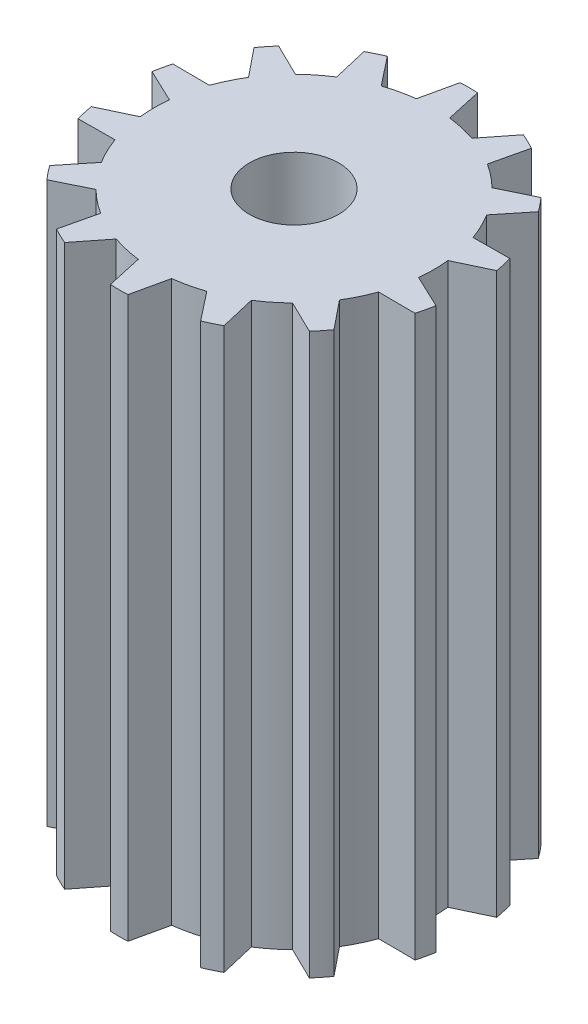
SolidWorks part; units mm, degrees
ref_plane "Front Plane" through (0, 0, 0) normal (0, 0, 1) x (1, 0, 0)
ref_plane "Top Plane" through (0, 0, 0) normal (0, 1, 0) x (1, 0, 0)
ref_plane "Right Plane" through (0, 0, 0) normal (1, 0, 0) x (0, 0, -1)
sketch "Sketch1" plane through (0, 0, 0) normal (0, 1, 0) x (1, 0, 0)
  line L0 (0, 0.0394) -> (0, 50000.0394) construction
  line L1 (0.0484, 0) -> (50000.0484, 0) construction
  line L30 (-0.25, 4.9937) -> (-0.4766, 3.9715)
  line L31 (0.25, 4.9937) -> (0.4766, 3.9715)
  line L32 (2.3919, 4.3907) -> (2.1526, 3.3714)
  line L33 (1.9415, 4.6077) -> (1.2937, 3.785)
  line L34 (4.0601, 2.9181) -> (3.4022, 2.1035)
  line L35 (3.7484, 3.309) -> (2.8079, 2.8488)
  line L36 (4.9242, 0.8675) -> (3.978, 0.4191)
  line L37 (4.8129, 1.3549) -> (3.7659, 1.3484)
  line L38 (4.8129, -1.3549) -> (3.7659, -1.3484)
  line L39 (4.9242, -0.8675) -> (3.978, -0.4191)
  line L40 (3.7484, -3.309) -> (2.8079, -2.8488)
  line L41 (4.0601, -2.9181) -> (3.4022, -2.1035)
  line L42 (1.9415, -4.6077) -> (1.2937, -3.785)
  line L43 (2.3919, -4.3907) -> (2.1526, -3.3714)
  line L44 (-0.25, -4.9937) -> (-0.4766, -3.9715)
  line L45 (0.25, -4.9937) -> (0.4766, -3.9715)
  line L46 (-2.3919, -4.3907) -> (-2.1526, -3.3714)
  line L47 (-1.9415, -4.6077) -> (-1.2937, -3.785)
  line L48 (-4.0601, -2.9181) -> (-3.4022, -2.1035)
  line L49 (-3.7484, -3.309) -> (-2.8079, -2.8488)
  line L50 (-4.9242, -0.8675) -> (-3.978, -0.4191)
  line L51 (-4.8129, -1.3549) -> (-3.7659, -1.3484)
  line L52 (-4.8129, 1.3549) -> (-3.7659, 1.3484)
  line L53 (-4.9242, 0.8675) -> (-3.978, 0.4191)
  line L54 (-3.7484, 3.309) -> (-2.8079, 2.8488)
  line L55 (-4.0601, 2.9181) -> (-3.4022, 2.1035)
  line L56 (-1.9415, 4.6077) -> (-1.2937, 3.785)
  line L57 (-2.3919, 4.3907) -> (-2.1526, 3.3714)
  circle A29 centre (0, 0) radius 4.5 construction
  arc A30 (-0.4766, 3.9715) -> (-1.2937, 3.785) centre (0, 0) ccw
  arc A31 (0.25, 4.9937) -> (-0.25, 4.9937) centre (0, 0) ccw
  arc A32 (2.3919, 4.3907) -> (1.9415, 4.6077) centre (0, 0) ccw
  arc A33 (4.0601, 2.9181) -> (3.7484, 3.309) centre (0, 0) ccw
  arc A34 (4.9242, 0.8675) -> (4.8129, 1.3549) centre (0, 0) ccw
  arc A35 (4.8129, -1.3549) -> (4.9242, -0.8675) centre (0, 0) ccw
  arc A36 (3.7484, -3.309) -> (4.0601, -2.9181) centre (0, 0) ccw
  arc A37 (1.9415, -4.6077) -> (2.3919, -4.3907) centre (0, 0) ccw
  arc A38 (-0.25, -4.9937) -> (0.25, -4.9937) centre (0, 0) ccw
  arc A39 (-2.3919, -4.3907) -> (-1.9415, -4.6077) centre (0, 0) ccw
  arc A40 (-4.0601, -2.9181) -> (-3.7484, -3.309) centre (0, 0) ccw
  arc A41 (-4.9242, -0.8675) -> (-4.8129, -1.3549) centre (0, 0) ccw
  arc A42 (-4.8129, 1.3549) -> (-4.9242, 0.8675) centre (0, 0) ccw
  arc A43 (-3.7484, 3.309) -> (-4.0601, 2.9181) centre (0, 0) ccw
  arc A44 (-1.9415, 4.6077) -> (-2.3919, 4.3907) centre (0, 0) ccw
  arc A45 (1.2937, 3.785) -> (0.4766, 3.9715) centre (0, 0) ccw
  arc A46 (2.8079, 2.8488) -> (2.1526, 3.3714) centre (0, 0) ccw
  arc A47 (-2.1526, 3.3714) -> (-2.8079, 2.8488) centre (0, 0) ccw
  arc A48 (-3.4022, 2.1035) -> (-3.7659, 1.3484) centre (0, 0) ccw
  arc A49 (-3.978, 0.4191) -> (-3.978, -0.4191) centre (0, 0) ccw
  arc A50 (-3.7659, -1.3484) -> (-3.4022, -2.1035) centre (0, 0) ccw
  arc A51 (-2.8079, -2.8488) -> (-2.1526, -3.3714) centre (0, 0) ccw
  arc A52 (-1.2937, -3.785) -> (-0.4766, -3.9715) centre (0, 0) ccw
  arc A53 (0.4766, -3.9715) -> (1.2937, -3.785) centre (0, 0) ccw
  arc A54 (2.1526, -3.3714) -> (2.8079, -2.8488) centre (0, 0) ccw
  arc A55 (3.4022, -2.1035) -> (3.7659, -1.3484) centre (0, 0) ccw
  arc A56 (3.978, -0.4191) -> (3.978, 0.4191) centre (0, 0) ccw
  arc A57 (3.7659, 1.3484) -> (3.4022, 2.1035) centre (0, 0) ccw
  point P75 (0, 0)
  dimension "D1" = 9
extrude "Boss-Extrude1" add sketch "Sketch1" along normal blind 16
sketch "Sketch2" plane through (0, 0, 0) normal (0, -1, 0) x (1, 0, 0)
  circle A0 centre (0, 0) radius 1.275
  dimension "D1" = 2.55
extrude "Cut-Extrude1" cut sketch "Sketch2" against normal through all
